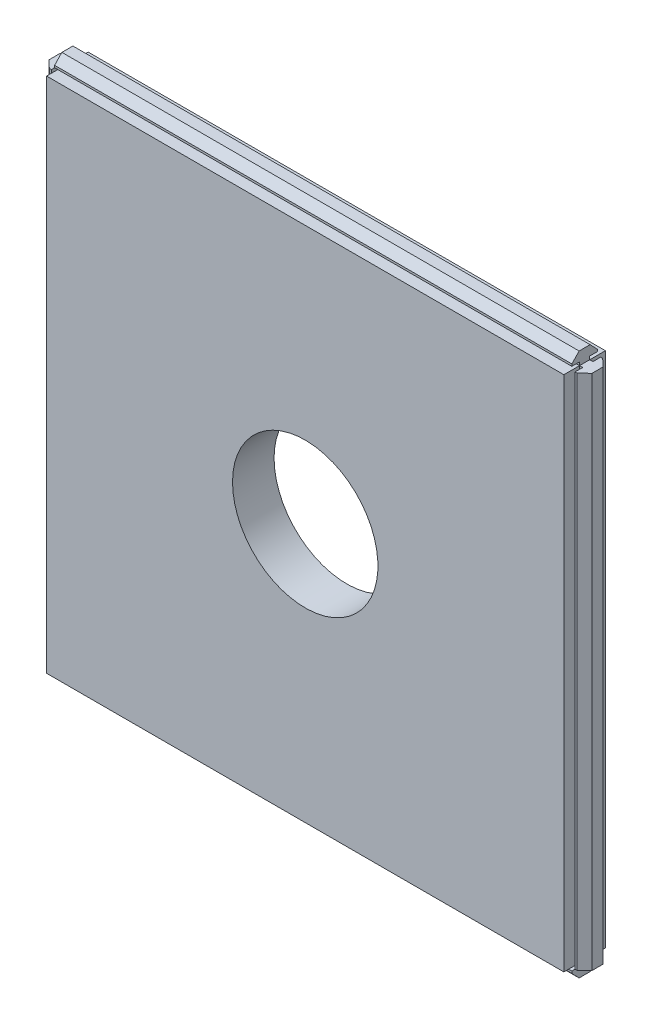
SolidWorks part; units mm, degrees
ref_plane "Plan de face" through (0, 0, 0) normal (0, 0, 1) x (1, 0, 0)
ref_plane "Plan de dessus" through (0, 0, 0) normal (0, 1, 0) x (1, 0, 0)
ref_plane "Plan de droite" through (0, 0, 0) normal (1, 0, 0) x (0, 0, -1)
sketch "Esquisse1" plane through (0, 0, 0) normal (0, 0, 1) x (1, 0, 0)
  line L0 (-263.0604, 145.3585) -> (-14.0604, 145.3585)
  line L1 (-14.0604, 145.3585) -> (-14.0604, 139.1585)
  line L2 (-14.0604, 139.1585) -> (-7.8604, 139.1585)
  line L3 (-7.8604, 139.1585) -> (-7.8604, -109.8415)
  line L4 (-7.8604, -109.8415) -> (-14.0604, -109.8415)
  line L5 (-14.0604, -109.8415) -> (-14.0604, -116.0415)
  line L6 (-14.0604, -116.0415) -> (-263.0604, -116.0415)
  line L7 (-263.0604, -116.0415) -> (-263.0604, -109.8415)
  line L8 (-263.0604, -109.8415) -> (-269.2604, -109.8415)
  line L9 (-269.2604, -109.8415) -> (-269.2604, 139.1585)
  line L10 (-269.2604, 139.1585) -> (-263.0604, 139.1585)
  line L11 (-263.0604, 139.1585) -> (-263.0604, 145.3585)
  dimension "D1" = 249
  dimension "D2" = 6.2
  dimension "D3" = 6.2
  dimension "D4" = 6.2
  dimension "249" = 249
  dimension "D5" = 6.2
  dimension "D6" = 249
  dimension "D7" = 6.2
  dimension "D8" = 6.2
  dimension "D9" = 249
  dimension "D10" = 6.2
  dimension "D11" = 6.2
extrude "Boss.-Extru.3" add sketch "Esquisse1" along normal blind 20
sketch "Esquisse4" plane through (-14.0604, 0, 0) normal (1, 0, 0) x (0, 0, -1)
  line L0 (-20, 139.1585) -> (-12.45, 139.1585)
  line L1 (-12.45, 139.1585) -> (-12.45, 140.7085)
  line L2 (-12.45, 140.7085) -> (-16.15, 140.7085)
  line L3 (-16.15, 140.7085) -> (-16.15, 141.7085)
  line L4 (-16.15, 141.7085) -> (-12.65, 145.3585)
  line L5 (-20, 145.3585) -> (0, 145.3585) construction
  dimension "D1" = 7.55
  dimension "D2" = 1.55
  dimension "D3" = 3.7
  dimension "D4" = 1
  dimension "D5" = 7.35
extrude "Enlèv. mat.-Extru.11" cut sketch "Esquisse4" against normal blind 249 and the other way through all
sketch "Esquisse8" plane through (-14.0604, 0, 0) normal (1, 0, 0) x (0, 0, -1)
  line L0 (0, 139.1585) -> (-7.55, 139.1585)
  line L1 (-12.45, 139.1585) -> (0, 139.1585) construction
  line L2 (-7.55, 139.1585) -> (-7.55, 140.7085)
  line L3 (-7.55, 140.7085) -> (-3.85, 140.7085)
  line L4 (-3.85, 140.7085) -> (-3.85, 141.7085)
  line L5 (-3.85, 141.7085) -> (-7.35, 145.3585)
  line L6 (-12.65, 145.3585) -> (0, 145.3585) construction
  dimension "D1" = 7.55
  dimension "D2" = 1.55
  dimension "D3" = 3.7
  dimension "D4" = 1
  dimension "D5" = 7.35
extrude "Enlèv. mat.-Extru.12" cut sketch "Esquisse8" against normal blind 249 and the other way through all flip side to cut
sketch "Esquisse10" plane through (0, 139.1585, 0) normal (0, 1, 0) x (1, 0, 0)
  line L0 (-263.0604, -12.45) -> (-263.0604, -20)
  line L1 (-7.8604, -20) -> (-269.2604, -20) construction
  line L2 (-263.0604, -12.45) -> (-264.6104, -12.45)
  line L3 (-264.6104, -12.45) -> (-264.6104, -16.15)
  line L4 (-264.6104, -16.15) -> (-265.6104, -16.15)
  line L5 (-265.6104, -16.15) -> (-269.2604, -12.65)
  line L6 (-269.2604, -20) -> (-269.2604, 0) construction
  dimension "D1" = 1.55
  dimension "D2" = 3.7
  dimension "D3" = 1
  dimension "D4" = 7.35
extrude "Enlèv. mat.-Extru.13" cut sketch "Esquisse10" against normal blind 249 and the other way through all
sketch "Esquisse11" plane through (0, 139.1585, 0) normal (0, 1, 0) x (1, 0, 0)
  line L0 (-263.0604, -7.55) -> (-263.0604, 0)
  line L1 (-7.8604, 0) -> (-269.2604, 0) construction
  line L2 (-263.0604, -7.55) -> (-264.6104, -7.55)
  line L3 (-264.6104, -7.55) -> (-264.6104, -3.85)
  line L4 (-264.6104, -3.85) -> (-265.8133, -3.85)
  line L5 (-265.8133, -3.85) -> (-269.2604, -7.35)
  line L6 (-269.2604, -12.65) -> (-269.2604, 0) construction
  dimension "D1" = 7.55
  dimension "D2" = 1.55
  dimension "D3" = 3.7
  dimension "D4" = 1.203
  dimension "D5" = 7.35
extrude "Enlèv. mat.-Extru.14" cut sketch "Esquisse11" against normal blind 249 and the other way through all flip side to cut
sketch "Esquisse12" plane through (-263.0604, 0, 0) normal (-1, 0, 0) x (0, 0, 1)
  line L0 (12.45, -109.8415) -> (20, -109.8415)
  line L1 (20, 139.1585) -> (20, -116.0415) construction
  line L2 (12.45, -109.8415) -> (12.45, -111.3915)
  line L3 (12.45, -111.3915) -> (16.15, -111.3915)
  line L4 (16.15, -111.3915) -> (16.15, -112.3915)
  line L5 (16.15, -112.3915) -> (12.65, -116.0415)
  line L6 (20, -116.0415) -> (0, -116.0415) construction
  dimension "D1" = 7.55
  dimension "D2" = 1.55
  dimension "D3" = 3.7
  dimension "D4" = 1
  dimension "D5" = 7.35
extrude "Enlèv. mat.-Extru.15" cut sketch "Esquisse12" against normal blind 249 and the other way through all
sketch "Esquisse13" plane through (-263.0604, 0, 0) normal (-1, 0, 0) x (0, 0, 1)
  line L0 (7.55, -109.8415) -> (0, -109.8415)
  line L1 (0, 139.1585) -> (0, -116.0415) construction
  line L2 (7.55, -109.8415) -> (7.55, -111.3915)
  line L3 (7.55, -111.3915) -> (3.85, -111.3915)
  line L4 (3.85, -111.3915) -> (3.85, -112.3915)
  line L5 (3.85, -112.3915) -> (7.35, -116.0415)
  line L6 (12.65, -116.0415) -> (0, -116.0415) construction
  dimension "D1" = 7.55
  dimension "D2" = 1.55
  dimension "D3" = 3.7
  dimension "D4" = 1
  dimension "D5" = 7.35
extrude "Enlèv. mat.-Extru.16" cut sketch "Esquisse13" against normal blind 249 and the other way through all flip side to cut
sketch "Esquisse15" plane through (0, 139.1585, 0) normal (0, 1, 0) x (1, 0, 0)
  line L0 (-14.0604, -7.55) -> (-14.0604, 0)
  line L1 (-7.8604, 0) -> (-263.0604, 0) construction
  line L2 (-14.0604, -7.55) -> (-12.5104, -7.55)
  line L3 (-12.5104, -7.55) -> (-12.5104, -3.85)
  line L4 (-12.5104, -3.85) -> (-11.5104, -3.85)
  line L5 (-11.5104, -3.85) -> (-7.8604, -7.35)
  line L6 (-7.8604, -20) -> (-7.8604, 0) construction
  dimension "D1" = 1.55
  dimension "D2" = 3.7
  dimension "D3" = 1
  dimension "D4" = 7.35
extrude "Enlèv. mat.-Extru.17" cut sketch "Esquisse15" against normal blind 249 and the other way through all
sketch "Esquisse16" plane through (0, 139.1585, 0) normal (0, 1, 0) x (1, 0, 0)
  line L0 (-14.0604, -12.45) -> (-14.0604, -20)
  line L1 (-7.8604, -20) -> (-263.0604, -20) construction
  line L2 (-14.0604, -12.45) -> (-12.5104, -12.45)
  line L3 (-12.5104, -12.45) -> (-12.5104, -16.15)
  line L4 (-12.5104, -16.15) -> (-11.5104, -16.15)
  line L5 (-11.5104, -16.15) -> (-7.8604, -12.65)
  line L6 (-7.8604, -20) -> (-7.8604, -7.35) construction
  dimension "D1" = 1.55
  dimension "D2" = 3.7
  dimension "D3" = 1
  dimension "D4" = 7.35
extrude "Enlèv. mat.-Extru.18" cut sketch "Esquisse16" against normal blind 249 and the other way through all flip side to cut
sketch "Esquisse17" plane through (0, 0, 0) normal (0, 0, -1) x (-1, 0, 0)
  line L0 (14.0604, 139.1585) -> (263.0604, 139.1585) construction
  line L1 (263.0604, 139.1585) -> (263.0604, -109.8415) construction
  circle A0 centre (138.5604, 14.6585) radius 35
  dimension "D1" = 124.5
  dimension "D3" = 70
  dimension "D2" = 124.5
extrude "Enlèv. mat.-Extru.20" cut sketch "Esquisse17" against normal blind 20
